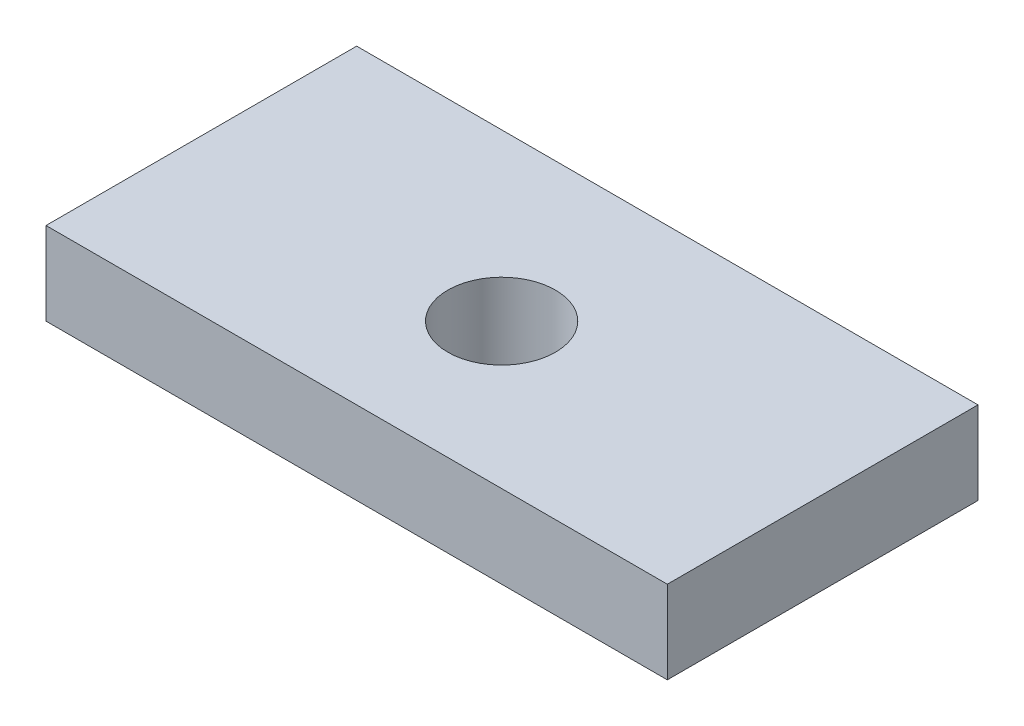
SolidWorks part; units mm, degrees
ref_plane "前视基准面" through (0, 0, 0) normal (0, 0, 1) x (1, 0, 0)
ref_plane "上视基准面" through (0, 0, 0) normal (0, 1, 0) x (1, 0, 0)
ref_plane "右视基准面" through (0, 0, 0) normal (1, 0, 0) x (0, 0, -1)
other "Configuration Table"
sketch "草图1" plane through (0, 0, 0) normal (0, 1, 0) x (1, 0, 0)
  line L1 (0, 0) -> (30, 0)
  line L2 (0, 0) -> (0, 15)
  line L3 (0, 15) -> (30, 15)
  line L4 (30, 0) -> (30, 15)
  circle A0 centre (15, 7) radius 2.6
  point P7 (15, 7)
  dimension "D3" = 5.2
  dimension "D1" = 30
  dimension "D2" = 15
extrude "凸台-拉伸1" add sketch "草图1" along normal blind 4
